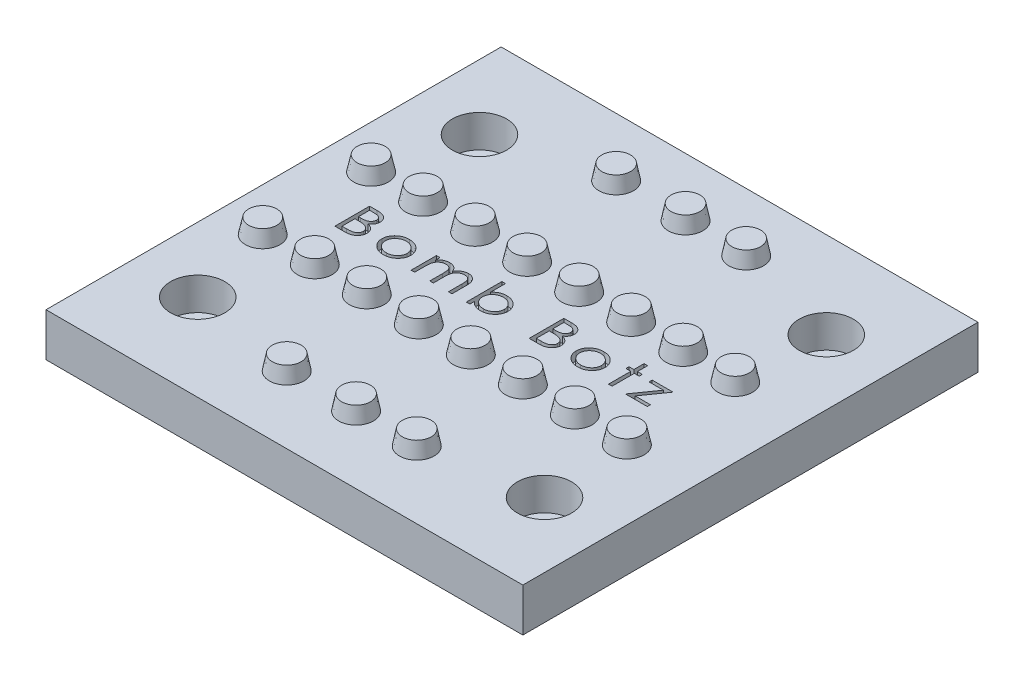
SolidWorks part; units mm, degrees
ref_plane "Front Plane" through (0, 0, 0) normal (0, 0, 1) x (1, 0, 0)
ref_plane "Top Plane" through (0, 0, 0) normal (0, 1, 0) x (1, 0, 0)
ref_plane "Right Plane" through (0, 0, 0) normal (1, 0, 0) x (0, 0, -1)
sketch "Sketch3" plane through (0, 0, 0) normal (0, 1, 0) x (1, 0, 0)
  line L1 (-22.2096, 15.089) -> (47.6404, 15.089)
  line L2 (-22.2096, 15.089) -> (-22.2096, -51.586)
  line L3 (-22.2096, -51.586) -> (47.6404, -51.586)
  line L4 (47.6404, 15.089) -> (47.6404, -51.586)
  dimension "D1" = 69.85
  dimension "D2" = 66.675
extrude "Boss-Extrude2" add sketch "Sketch3" along normal blind 6.35
sketch "Sketch5" plane through (0, 6.35, 0) normal (0, 1, 0) x (1, 0, 0)
  line L0 (-22.2096, 15.089) -> (-22.2096, -51.586) construction
  line L1 (47.6404, 15.089) -> (-22.2096, 15.089) construction
  circle A0 centre (-12.6846, 2.389) radius 3.9688
  circle A1 centre (38.1154, 2.389) radius 3.9687
  circle A2 centre (-12.6846, -38.886) radius 3.9688
  circle A3 centre (38.1154, -38.886) radius 3.9688
  point P8 (35.1659, 2.389)
  point P11 (-12.6846, -37.9513)
  point P14 (38.1154, -38.886)
  dimension "D1" = 7.9375
  dimension "D2" = 9.525
  dimension "D3" = 12.7
  dimension "D4" = 50.8
  dimension "D5" = 41.275
extrude "Cut-Extrude1" cut sketch "Sketch5" against normal blind 4.7625
sketch "Sketch6" plane through (0, 1.5875, 0) normal (0, 1, 0) x (1, 0, 0)
  line L0 (-22.2096, 15.089) -> (-22.2096, -51.586) construction
  line L1 (47.6404, 15.089) -> (-22.2096, 15.089) construction
  circle A0 centre (-12.6846, 2.389) radius 2.54
  circle A1 centre (38.1154, 2.389) radius 2.54
  circle A2 centre (38.1154, -38.886) radius 2.54
  circle A3 centre (-12.6846, -38.886) radius 2.54
  point P2 (0, 0)
  point P3 (0, 0)
  point P8 (-5.0488, 18.2892)
  point P11 (38.1154, 2.389)
  point P15 (38.1154, -38.886)
  point P19 (-12.6846, -38.886)
  dimension "D1" = 9.525
  dimension "D2" = 12.7
  dimension "D3" = 50.8
extrude "Cut-Extrude2" cut sketch "Sketch6" against normal through all
sketch "Sketch7" plane through (0, 6.35, 0) normal (0, 1, 0) x (1, 0, 0)
  line L0 (-22.2096, -51.586) -> (47.6404, -51.586) construction
  line L1 (47.6404, 15.089) -> (-22.2096, 15.089) construction
  line L2 (-22.2096, 15.089) -> (-22.2096, -51.586) construction
  circle A0 centre (-15.8596, -26.186) radius 2.54
  circle A1 centre (-15.8596, -10.311) radius 2.54
  dimension "D1" = 5.08
  dimension "D2" = 5.08
  dimension "D3" = 25.4
  dimension "D4" = 25.4
  dimension "D5" = 6.35
  dimension "D6" = 6.35
extrude "Boss-Extrude3" add sketch "Sketch7" along normal blind 2.2225 draft 12
pattern_linear "LPattern1" count 8 spacing 7.62 along (1, 0, 0) of "Boss-Extrude3"
sketch "Sketch8" plane through (0, 6.35, 0) normal (0, 1, 0) x (1, 0, 0)
  line L0 (47.6404, -51.586) -> (47.6404, 15.089) construction
  line L1 (-22.2096, 15.089) -> (-22.2096, -51.586) construction
  circle A0 centre (3.1904, -41.7237) radius 2.54
  circle A1 centre (22.2404, -41.7237) radius 2.54
  circle A2 centre (13.3504, -41.7237) radius 2.54
  dimension "D1" = 5.08
  dimension "D2" = 5.08
  dimension "D3" = 5.08
  dimension "D4" = 25.4
  dimension "D5" = 25.4
  dimension "D6" = 8.89
extrude "Boss-Extrude4" add sketch "Sketch8" along normal blind 2.2225 draft 11
pattern_linear "LPattern2" count 2 spacing 48.26 along (0, 0, -1) of "Boss-Extrude4"
sketch "Sketch9" plane through (0, 6.35, 0) normal (0, 1, 0) x (1, 0, 0)
  text T0 "Bomb Botz" font "Century Gothic" height 5.08
extrude "Cut-Extrude3" cut sketch "Sketch9" against normal blind 1.27
